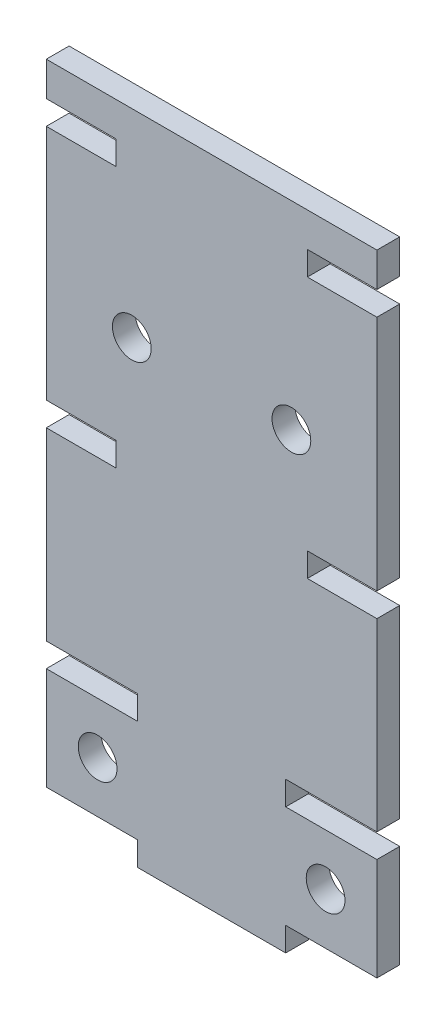
SolidWorks part; units mm, degrees
ref_plane "前视基准面" through (0, 0, 0) normal (0, 0, 1) x (1, 0, 0)
ref_plane "上视基准面" through (0, 0, 0) normal (0, 1, 0) x (1, 0, 0)
ref_plane "右视基准面" through (0, 0, 0) normal (1, 0, 0) x (0, 0, -1)
other "Configuration Table"
sketch "草图1" plane through (0, 0, 0) normal (0, 0, 1) x (1, 0, 0)
  line L0 (0, 0) -> (29, 0)
  line L1 (29, 0) -> (29, 39.1)
  line L2 (29, 39.1) -> (0, 39.1)
  line L3 (0, 39.1) -> (0, 0)
  line L4 (46.9198, 19.55) -> (-22.434, 19.55) construction
  line L5 (14.5, 49.2453) -> (14.5, -17.6462) construction
  line L6 (8, 0) -> (8, -2.1)
  line L7 (8, -2.1) -> (21, -2.1)
  line L8 (21, 0) -> (21, -2.1)
  line L9 (8, 11.1) -> (0, 11.1)
  line L10 (8, 11.1) -> (8, 9)
  line L11 (8, 9) -> (0, 9)
  line L12 (21, 9) -> (29, 9)
  line L13 (21, 11.1) -> (29, 11.1)
  line L14 (21, 11.1) -> (21, 9)
  line L15 (8, 9) -> (21, 9)
  line L16 (8, 11.1) -> (21, 11.1)
  point P13 (14.5, -2.1)
  dimension "D1" = 29
  dimension "D2" = 2.1
  dimension "D3" = 8
  dimension "D4" = 2.1
  dimension "D5" = 9
  dimension "D6" = 28
extrude "凸台-拉伸3" add sketch "草图1" along normal blind 2 contours L9 L16 L13 L1 L2 L3 | L8 L0 L6 L7 | L15 L11 L3 L0 L1 L12 | L13 L14 L12 L1 | L11 L10 L9 L3
sketch "草图2" plane through (0, 0, 2) normal (0, 0, 1) x (1, 0, 0)
  line L0 (6.1, 18.3) -> (0, 18.3)
  line L1 (0, 39.1) -> (0, 0) construction
  line L2 (6.1, 18.3) -> (6.1, 16.2)
  line L3 (6.1, 16.2) -> (0, 16.2)
  line L4 (14.5, 52.9051) -> (14.5, -12.476) construction
  line L5 (29, 0) -> (29, 39.1) construction
  line L6 (21, 11.1) -> (8, 11.1) construction
  line L7 (22.9, 18.3) -> (22.9, 16.2)
  line L8 (22.9, 16.2) -> (29, 16.2)
  line L9 (22.9, 18.3) -> (29, 18.3)
  line L10 (0, 18.3) -> (0, 16.2)
  line L11 (29, 18.3) -> (29, 16.2)
  dimension "D1" = 5.1
  dimension "D2" = 2.1
  dimension "D3" = 6.1
extrude "切除-拉伸1" cut sketch "草图2" against normal blind 2
sketch "草图3" plane through (0, 0, 2) normal (0, 0, 1) x (1, 0, 0)
  line L0 (14.5, 39.1) -> (14.5, 56.1053) construction
  line L1 (29, 39.1) -> (0, 39.1) construction
  line L2 (6.1, 39.1) -> (6.1, 41.2)
  line L3 (6.1, 41.2) -> (22.9, 41.2)
  line L4 (22.9, 39.1) -> (22.9, 41.2)
  line L5 (6.1, 39.1) -> (22.9, 39.1)
  point P9 (14.5, 41.2)
  dimension "D1" = 16.8
  dimension "D2" = 2.1
sketch "草图12" plane through (0, 0, 2) normal (0, 0, 1) x (1, 0, 0)
  line L0 (8, 11.1) -> (8, 9)
  line L1 (8, 9) -> (21, 9)
  line L2 (21, 9) -> (21, 11.1)
  line L3 (21, 11.1) -> (8, 11.1)
extrude "凸台-拉伸9" add sketch "草图12" against normal blind 2
sketch "草图13" plane through (0, 0, 2) normal (0, 0, 1) x (1, 0, 0)
  line L0 (8, -2.1) -> (0, -2.1)
  line L1 (0, -2.1) -> (0, -11.1)
  line L2 (0, -11.1) -> (8, -11.1)
  line L3 (8, -11.1) -> (8, -13.2)
  line L4 (8, -13.2) -> (21, -13.2)
  line L5 (14.5, -2.1) -> (14.5, -13.5924) construction
  line L6 (8, -2.1) -> (21, -2.1) construction
  line L7 (8, 0) -> (8, -2.1) construction
  line L8 (3.6298, -6.6) -> (26.4399, -6.6) construction
  line L9 (21, -2.1) -> (29, -2.1)
  line L10 (25.3702, -6.6) -> (2.5601, -6.6) construction
  line L11 (21, -11.1) -> (21, -13.2)
  line L12 (29, -11.1) -> (21, -11.1)
  line L13 (29, -2.1) -> (29, -11.1)
  line L14 (8, -2.1) -> (21, -2.1)
  circle A0 centre (4.5, -6.6) radius 1.7
  circle A1 centre (24.5, -6.6) radius 1.7
  point P25 (14.5, -13.2)
  dimension "D3" = 3.4
  dimension "D1" = 9
  dimension "D2" = 2.1
  dimension "D4" = 20
extrude "凸台-拉伸10" add sketch "草图13" against normal blind 2
extrude "凸台-拉伸4" add sketch "草图3" against normal blind 2
sketch "草图8" plane through (0, 0, 2) normal (0, 0, 1) x (1, 0, 0)
  line L0 (29, 18.3) -> (22.9, 18.3) construction
  line L3 (14.5, 41.2) -> (14.5, 18.5479) construction
  line L4 (22.9, 41.2) -> (6.1, 41.2) construction
  circle A0 centre (21.5, 26.8) radius 1.7
  circle A1 centre (7.5, 26.8) radius 1.7
  dimension "D1" = 3.4
  dimension "D2" = 14
  dimension "D3" = 8.5
extrude "切除-拉伸4" cut sketch "草图8" against normal blind 10
sketch "草图9" plane through (0, 0, 2) normal (0, 0, 1) x (1, 0, 0)
  line L0 (6.1, 39.1) -> (22.9, 39.1)
  line L1 (22.9, 39.1) -> (22.9, 41.2)
  line L2 (22.9, 41.2) -> (6.1, 41.2)
  line L3 (6.1, 41.2) -> (6.1, 39.1)
extrude "切除-拉伸5" cut sketch "草图9" against normal blind 10
sketch "草图11" plane through (0, 0, 2) normal (0, 0, 1) x (1, 0, 0)
  line L0 (14.5, 39.1) -> (14.5, 49.0223) construction
  line L1 (29, 39.1) -> (0, 39.1) construction
  line L2 (6.1, 39.1) -> (6.1, 41.2)
  line L4 (6.1, 41.2) -> (0, 41.2)
  line L5 (0, 41.2) -> (0, 44.2)
  line L6 (0, 44.2) -> (29, 44.2)
  line L7 (6.1, 16.2) -> (6.1, 18.3) construction
  line L8 (6.1, 39.1) -> (22.9, 39.1)
  line L9 (22.9, 41.2) -> (29, 41.2)
  line L10 (22.9, 39.1) -> (22.9, 41.2)
  line L11 (29, 44.2) -> (29, 41.2)
  point P15 (14.5, 44.2)
  point P17 (14.5, 41.2)
  dimension "D1" = 3
  dimension "D2" = 2.1
extrude "凸台-拉伸11" add sketch "草图11" against normal blind 2
